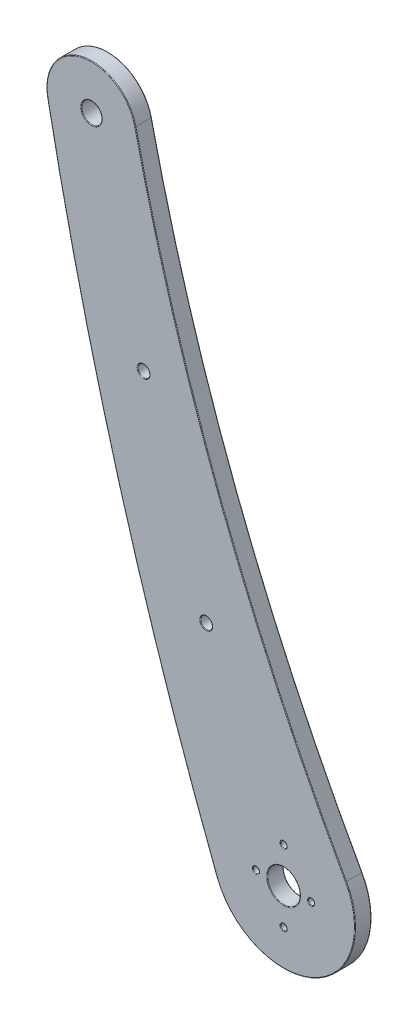
SolidWorks part; units mm, degrees
ref_plane "前视基准面" through (0, 0, 0) normal (0, 0, 1) x (1, 0, 0)
ref_plane "上视基准面" through (0, 0, 0) normal (0, 1, 0) x (1, 0, 0)
ref_plane "右视基准面" through (0, 0, 0) normal (1, 0, 0) x (0, 0, -1)
sketch "草图1" plane through (0, 0, 0) normal (0, 0, 1) x (1, 0, 0)
  line L0 (-21.1363, 59.5492) -> (-68.1415, 199.8863) construction
  line L1 (-21.1363, 59.5492) -> (-68.1415, 199.8863) construction
  line L2 (-21.1363, 59.5492) -> (-7.6363, 59.5492) construction
  line L3 (-21.1363, 59.5492) -> (-21.1363, 48.6984) construction
  circle A0 centre (-21.1363, 59.5492) radius 17.5 construction
  circle A1 centre (-68.1415, 199.8863) radius 11 construction
  circle A2 centre (-21.1363, 59.5492) radius 17.5 construction
  circle A3 centre (-68.1415, 199.8863) radius 11 construction
  circle A4 centre (-21.1363, 59.5492) radius 4
  circle A5 centre (-68.1415, 199.8863) radius 2.5
  arc A6 (-57.4125, 202.3127) -> (-5.8713, 68.1066) centre (430.2714, 312.6051) ccw
  arc A7 (-78.9418, 197.7995) -> (-37.4646, 53.2533) centre (755.6226, 359.0519) ccw
  arc A8 (-68.1415, 199.8863) -> (-21.1363, 59.5492) centre (663.0588, 366.7576) ccw construction
  arc A9 (-78.9418, 197.7995) -> (-57.4125, 202.3127) centre (-68.1415, 199.8863) cw
  arc A10 (-37.4646, 53.2533) -> (-5.8713, 68.1066) centre (-21.1363, 59.5492) ccw
  circle A11 centre (-14.3863, 59.5492) radius 0.75
  circle A12 centre (-21.1363, 50.7992) radius 0.75
  circle A13 centre (-27.8863, 59.5492) radius 0.75
  circle A14 centre (-21.1363, 68.2992) radius 0.75
  point P17 (-55.3981, 151.5375)
  point P18 (-40.0818, 105.8108)
  dimension "D1" = 8
  dimension "D2" = 5
  dimension "D3" = 850
  dimension "D4" = 500
  dimension "D5" = 750
  dimension "D8" = 1.5
  dimension "D6" = 50
  dimension "D7" = 50
  dimension "D9" = 8.75
  dimension "D10" = 6.75
extrude "凸台-拉伸1" add sketch "草图1" against normal blind 4
hole_wizard "M3.5 螺纹孔的螺纹孔钻头1" positions "草图4" profile "草图5" hole size "M3.5" standard "ISO" end condition through all
sketch "草图4" plane through (0, 0, 0) normal (0, 0, 1) x (1, 0, 0)
  point P0 (-55.3981, 151.5375)
  point P3 (-40.0818, 105.8108)
sketch "草图5" plane through (-55.3981, 151.5375, 0) normal (1, 0, 0) x (0, -1, 0)
  line L0 (0, 0) -> (0, 4)
  line L1 (0, 4) -> (1.45, 4)
  line L2 (1.45, 4) -> (1.45, 0)
  line L5 (1.45, 0) -> (0, 0)
  line L11 (0, -6.35) -> (0, 107.95) construction
  dimension "通孔孔直径" = 2.9
  dimension "通孔孔深度" = 4
fillet "圆角1" radius 0.15 24 edges at (-65.6415, 199.8863, 0) (-61.406, 124.6073, 0) (-13.6906, 43.7121, 0) (-36.4905, 133.3476, 0) (-70.3984, 210.6523, 0) (-17.1363, 59.5492, 0) (-38.6318, 105.8108, 0) (-53.9481, 151.5375, 0) (-65.6415, 199.8863, -4) (-17.1363, 59.5492, -4) (-36.4905, 133.3476, -4) (-13.6906, 43.7121, -4) (-61.406, 124.6073, -4) (-70.3984, 210.6523, -4) (-38.6318, 105.8108, -4) (-53.9481, 151.5375, -4) (-13.6363, 59.5492, 0) (-20.3863, 50.7992, 0) (-28.6363, 59.5492, 0) (-21.8863, 68.2992, 0) (-13.6363, 59.5492, -4) (-20.3863, 50.7992, -4) (-28.6363, 59.5492, -4) (-21.8863, 68.2992, -4)
